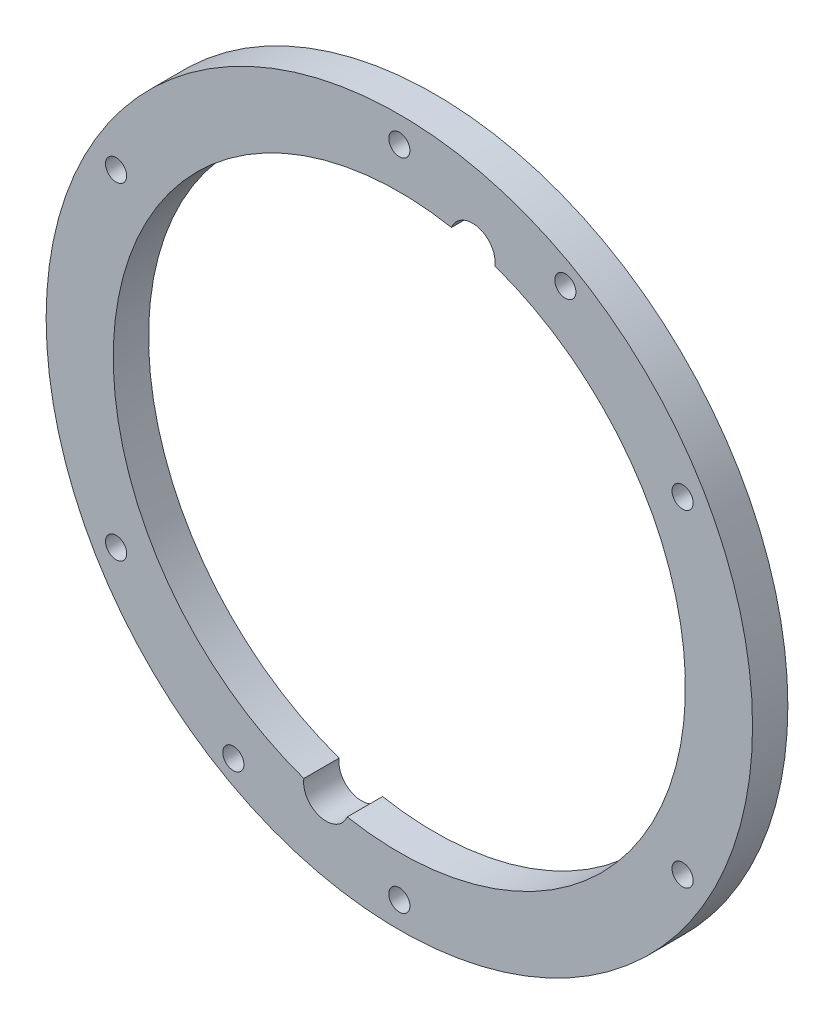
SolidWorks part; units mm, degrees
ref_plane "Plan de face" through (0, 0, 0) normal (0, 0, 1) x (1, 0, 0)
ref_plane "Plan de dessus" through (0, 0, 0) normal (0, 1, 0) x (1, 0, 0)
ref_plane "Plan de droite" through (0, 0, 0) normal (1, 0, 0) x (0, 0, -1)
sketch "Esquisse1" plane through (0, 0, 0) normal (0, 0, 1) x (1, 0, 0)
  line L0 (53.6751, 0) -> (-86.559, 0) construction
  line L1 (0, 50) -> (0, -56.2363) construction
  line L2 (0, 0) -> (70.5826, 40.7509) construction
  line L3 (0, 0) -> (-77.9761, 45.0195) construction
  line L10 (-33.3333, 0) -> (0, 0) construction
  circle A0 centre (0, 0) radius 50
  circle A1 centre (33.3333, 0) radius 16.6667 construction
  circle A2 centre (16.6667, -28.8675) radius 16.6667 construction
  circle A3 centre (-16.6667, -28.8675) radius 16.6667 construction
  circle A4 centre (-33.3333, 0) radius 16.6667 construction
  circle A5 centre (-16.6667, 28.8675) radius 16.6667 construction
  circle A6 centre (16.6667, 28.8675) radius 16.6667 construction
  circle A7 centre (-40.097, -23.15) radius 1.5
  circle A8 centre (-40.097, 23.15) radius 1.5
  circle A9 centre (0, 46.3) radius 1.5
  circle A10 centre (40.097, 23.15) radius 1.5
  circle A11 centre (40.097, -23.15) radius 1.5
  circle A12 centre (0, -46.3) radius 1.5
  circle A14 centre (0, 0) radius 16.6667 construction
  point P20 (0, 0)
  point P30 (0, 0)
  point P37 (0, 0)
  point P48 (-16.6667, 0)
  point P54 (0, 0)
  point P60 (0, 0)
  point P117 (0, 0)
  dimension "D1" = 6
  dimension "D2" = 30
  dimension "D4" = 6
  dimension "D3" = 30
extrude "Boss.-Extru.1" add sketch "Esquisse1" along normal blind 5
sketch "Sketch3" plane through (0, 0, 5) normal (0, 0, 1) x (1, 0, 0)
  line L0 (53.6751, 0) -> (-86.559, 0) construction
  line L6 (16.6667, 28.8675) -> (-16.6667, -28.8675) construction
  line L7 (-23.3333, 4) -> (-22.3333, 4)
  line L8 (-23.3333, 4) -> (-23.3333, -4)
  line L9 (-23.3333, -4) -> (-22.3333, -4)
  line L10 (-22.3333, 4) -> (-22.3333, -4)
  line L11 (-16.6667, 28.8675) -> (16.6667, -28.8675) construction
  line L12 (-13.2337, 23.9214) -> (-14.0997, 23.4214)
  line L13 (-14.0997, 23.4214) -> (-12.3497, 20.3903)
  line L14 (-12.3497, 20.3903) -> (-15.3808, 18.6403)
  line L15 (-15.3808, 18.6403) -> (-14.8808, 17.7742)
  line L16 (-14.8808, 17.7742) -> (-11.8497, 19.5242)
  line L17 (-11.8497, 19.5242) -> (-10.0997, 16.4932)
  line L18 (-10.0997, 16.4932) -> (-9.2337, 16.9932)
  line L19 (-9.2337, 16.9932) -> (-10.9837, 20.0242)
  line L20 (-10.9837, 20.0242) -> (-7.9526, 21.7742)
  line L21 (-7.9526, 21.7742) -> (-8.4526, 22.6403)
  line L22 (-8.4526, 22.6403) -> (-11.4837, 20.8903)
  line L23 (-11.4837, 20.8903) -> (-13.2337, 23.9214)
  line L24 (-16.2531, 17.5593) -> (-5.3419, 23.8588) construction
  line L25 (-14.6252, 25.3316) -> (-8.4936, 14.7114) construction
  line L26 (15.1308, 18.2073) -> (14.6308, 17.3412)
  line L27 (15.1308, 18.2073) -> (8.2026, 22.2073)
  line L28 (8.2026, 22.2073) -> (7.7026, 21.3412)
  line L29 (14.6308, 17.3412) -> (7.7026, 21.3412)
  line L30 (8.2026, -22.2073) -> (7.7026, -21.3412)
  line L31 (8.2026, -22.2073) -> (15.1308, -18.2073)
  line L32 (15.1308, -18.2073) -> (14.6308, -17.3412)
  line L33 (7.7026, -21.3412) -> (14.6308, -17.3412)
  line L34 (27.3333, -0.5) -> (27.3333, 0.5)
  line L35 (27.3333, 0.5) -> (23.8333, 0.5)
  line L36 (23.8333, 0.5) -> (23.8333, 4)
  line L37 (23.8333, 4) -> (22.8333, 4)
  line L38 (22.8333, 4) -> (22.8333, 0.5)
  line L39 (22.8333, 0.5) -> (19.3333, 0.5)
  line L40 (19.3333, 0.5) -> (19.3333, -0.5)
  line L41 (19.3333, -0.5) -> (22.8333, -0.5)
  line L42 (22.8333, -0.5) -> (22.8333, -4)
  line L43 (22.8333, -4) -> (23.8333, -4)
  line L44 (23.8333, -4) -> (23.8333, -0.5)
  line L45 (23.8333, -0.5) -> (27.3333, -0.5)
  line L46 (-14.0997, -23.4214) -> (-13.2337, -23.9214)
  line L47 (-13.2337, -23.9214) -> (-11.4837, -20.8903)
  line L48 (-11.4837, -20.8903) -> (-8.4526, -22.6403)
  line L49 (-8.4526, -22.6403) -> (-7.9526, -21.7742)
  line L50 (-7.9526, -21.7742) -> (-10.9837, -20.0242)
  line L51 (-10.9837, -20.0242) -> (-9.2337, -16.9932)
  line L52 (-9.2337, -16.9932) -> (-10.0997, -16.4932)
  line L53 (-10.0997, -16.4932) -> (-11.8497, -19.5242)
  line L54 (-11.8497, -19.5242) -> (-14.8808, -17.7742)
  line L55 (-14.8808, -17.7742) -> (-15.3808, -18.6403)
  line L56 (-15.3808, -18.6403) -> (-12.3497, -20.3903)
  line L57 (-12.3497, -20.3903) -> (-14.0997, -23.4214)
  line L58 (-21.8333, 14.2784) -> (-24.4284, 9.7836) construction
  line L59 (173205.0808, -100000) -> (-173283.0568, 100045.0195) construction
  line L60 (-7.433, 11.8744) -> (-5.683, 8.8433)
  line L61 (-6.567, 12.3744) -> (-7.433, 11.8744)
  line L62 (-7.8805, 13.6494) -> (-1.7489, 3.0291) construction
  line L63 (-2.567, 5.4462) -> (-4.317, 8.4772)
  line L64 (-1.2859, 10.2272) -> (-1.7859, 11.0933)
  line L65 (-3.433, 4.9462) -> (-2.567, 5.4462)
  line L66 (-4.317, 8.4772) -> (-1.2859, 10.2272)
  line L67 (-8.7141, 7.0933) -> (-8.2141, 6.2272)
  line L68 (-8.2141, 6.2272) -> (-5.183, 7.9772)
  line L69 (-4.817, 9.3433) -> (-6.567, 12.3744)
  line L70 (-1.7859, 11.0933) -> (-4.817, 9.3433)
  line L71 (-5.183, 7.9772) -> (-3.433, 4.9462)
  line L72 (-5.683, 8.8433) -> (-8.7141, 7.0933)
  line L73 (-9.0607, 6.3158) -> (-0.8395, 11.0623) construction
  line L74 (-173205.0808, -100000) -> (173275.6634, 100040.7509) construction
  text T0 "+"
  point P2 (-8.4641, 6.6603)
  point P4 (-1.5359, 10.6603)
  point P36 (-8.2026, 22.2073)
  point P39 (-13.6667, 23.6714)
  point P51 (0, 0)
  point P75 (0, 0)
  point P85 (-23.3333, 0)
  point P92 (-1.5413, 10.6572)
  dimension "D2" = 1
  dimension "D3" = 10
  dimension "D4" = 1
  dimension "D5" = 8
  dimension "D6" = 10
  dimension "D7" = 1
  dimension "D8" = 1
  dimension "D9" = 8
  dimension "D10" = 8
  dimension "D11" = 4
  dimension "D12" = 4
  dimension "D13" = 10
  dimension "D16" = 1
  dimension "D14" = 3
  dimension "D15" = 3
sketch "Sketch4" plane through (0, 0, 5) normal (0, 0, 1) x (1, 0, 0)
  line L0 (-0.3929, -0.6806) -> (-32.7522, -56.7285) construction
  line L1 (0, 0) -> (0, -46.3) construction
  line L2 (0, -60.3764) -> (0, 60.9995) construction
  circle A6 centre (-23.5, -40.7032) radius 1.5
  circle A7 centre (23.5, 40.7032) radius 1.5
  point P18 (0, 0)
  dimension "D2" = 47
  dimension "D1" = 30
  dimension "D3" = 46.3
extrude "Cut-Extrude4" cut sketch "Sketch4" against normal blind 10
sketch "Sketch5" plane through (0, 0, 5) normal (0, 0, 1) x (1, 0, 0)
  circle A0 centre (0, 0) radius 40.5
extrude "Cut-Extrude5" cut sketch "Sketch5" against normal blind 10
sketch "Sketch6" plane through (0, 0, 5) normal (0, 0, 1) x (1, 0, 0)
  line L0 (0, 0) -> (0, 54.3581) construction
  line L1 (0, 0) -> (18.4851, 68.9872) construction
  line L2 (0, 0) -> (-19.6547, 5.2665) construction
  circle A0 centre (10.3528, 38.637) radius 3.2
  circle A1 centre (-10.3528, -38.637) radius 3.2
  dimension "D2" = 40
  dimension "D1" = 15
extrude "Cut-Extrude6" cut sketch "Sketch6" against normal blind 10
